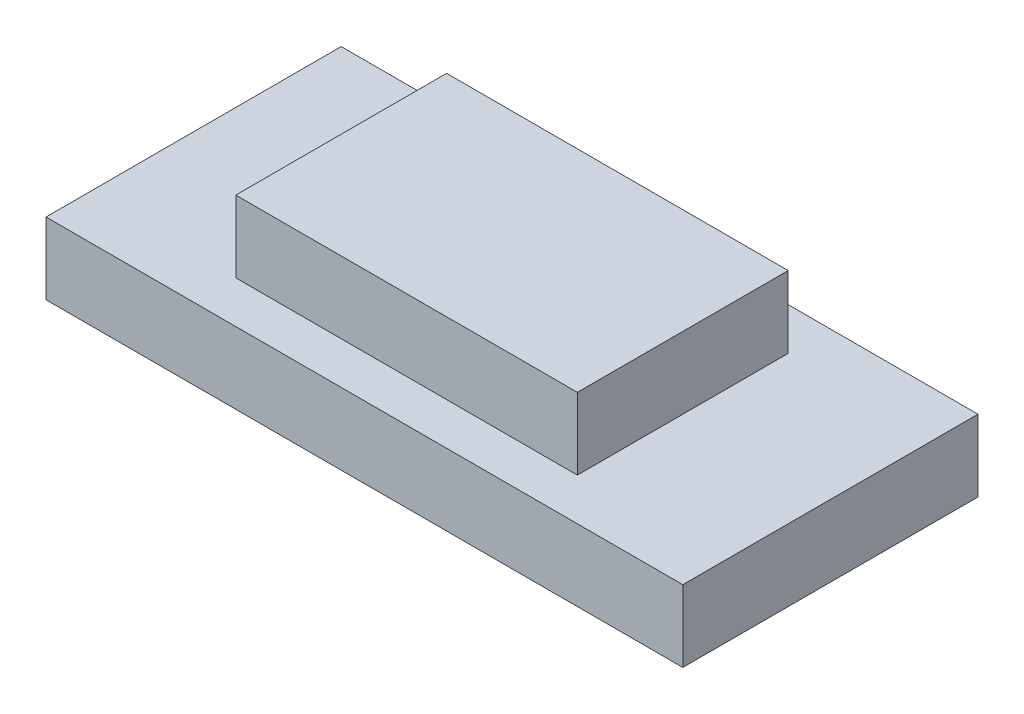
SolidWorks part; units mm, degrees
ref_plane "Front Plane" through (0, 0, 0) normal (0, 0, 1) x (1, 0, 0)
ref_plane "Top Plane" through (0, 0, 0) normal (0, 1, 0) x (1, 0, 0)
ref_plane "Right Plane" through (0, 0, 0) normal (1, 0, 0) x (0, 0, -1)
sketch "Sketch1" plane through (0, 0, 0) normal (0, 1, 0) x (1, 0, 0)
  line L1 (0, 0) -> (151, 0)
  line L2 (0, 0) -> (0, -70)
  line L3 (0, -70) -> (151, -70)
  line L4 (151, 0) -> (151, -70)
  dimension "D1" = 70
  dimension "D2" = 151
extrude "Boss-Extrude1" add sketch "Sketch1" along normal blind 17
sketch "Sketch2" plane through (0, 17, 0) normal (0, 1, 0) x (1, 0, 0)
  line L0 (151, 0) -> (0, 0) construction
  line L1 (35, -10) -> (116, -10)
  line L2 (35, -10) -> (35, -60)
  line L3 (35, -60) -> (116, -60)
  line L4 (116, -10) -> (116, -60)
  line L5 (0, -70) -> (151, -70) construction
  line L6 (0, 0) -> (0, -70) construction
  line L7 (151, -70) -> (151, 0) construction
  dimension "D1" = 10
  dimension "D2" = 10
  dimension "D3" = 35
  dimension "D4" = 35
extrude "Boss-Extrude2" add sketch "Sketch2" along normal blind 17
